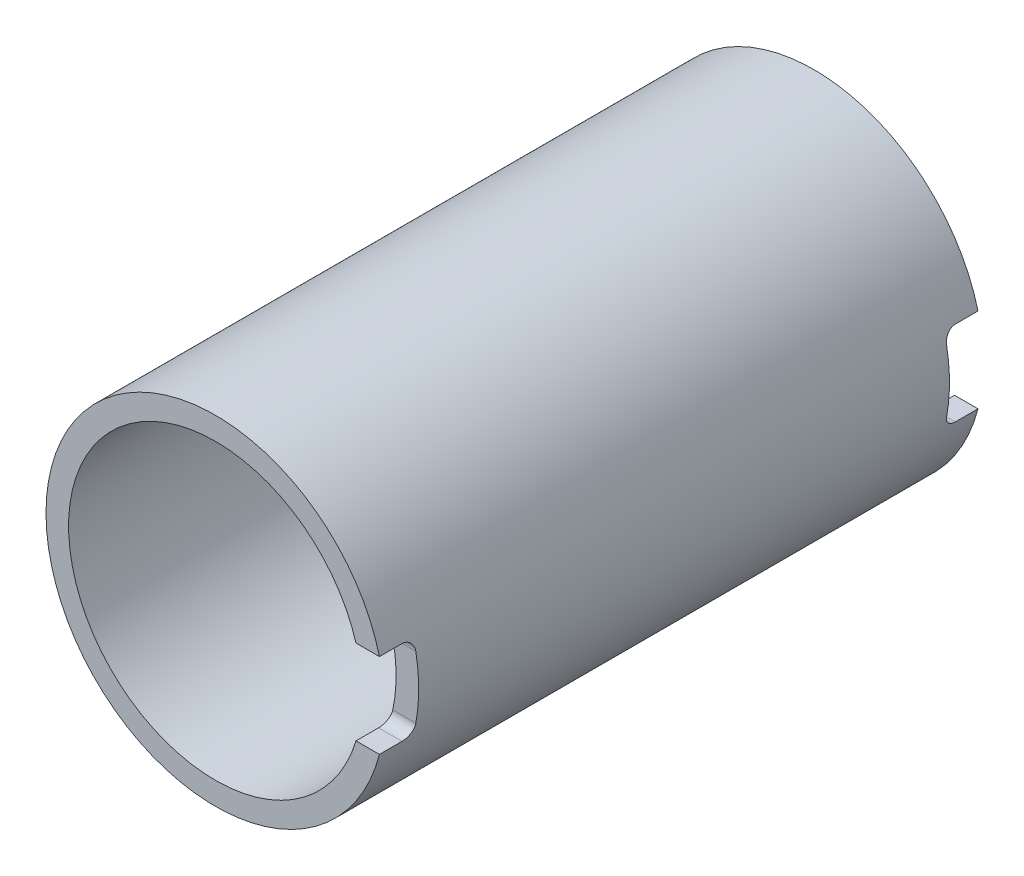
SolidWorks part; units mm, degrees
material "Brass"
ref_plane "Front Plane" through (0, 0, 0) normal (0, 0, 1) x (1, 0, 0)
ref_plane "Top Plane" through (0, 0, 0) normal (0, 1, 0) x (1, 0, 0)
ref_plane "Right Plane" through (0, 0, 0) normal (1, 0, 0) x (0, 0, -1)
sketch "Sketch2" plane through (0, 0, 0) normal (0, 0, 1) x (1, 0, 0)
  circle A0 centre (0, 0) radius 15
  circle A1 centre (0, 0) radius 13
  dimension "D1" = 30
  dimension "D2" = 26
extrude "Boss-Extrude1" add sketch "Sketch2" along normal mid plane 53
sketch "Sketch3" plane through (0, 0, 0) normal (1, 0, 0) x (0, 0, -1)
  line L0 (0, 0) -> (-50000, 0) construction
  line L1 (-26.5, -3.75) -> (-24.5, -3.75)
  line L2 (-26.5, 15) -> (-26.5, -15) construction
  line L3 (-23.5, -2.75) -> (-23.5, 2.75)
  line L4 (-26.5, 3.75) -> (-26.5, -3.75)
  line L5 (-24.5, 3.75) -> (-26.5, 3.75)
  line L6 (0, 0) -> (0, -50000) construction
  line L7 (26.5, -3.75) -> (24.5, -3.75)
  line L8 (23.5, -2.75) -> (23.5, 2.75)
  line L9 (26.5, 3.75) -> (26.5, -3.75)
  line L10 (24.5, 3.75) -> (26.5, 3.75)
  arc A0 (-24.5, -3.75) -> (-23.5, -2.75) centre (-24.5, -2.75) ccw
  arc A1 (-23.5, 2.75) -> (-24.5, 3.75) centre (-24.5, 2.75) ccw
  arc A2 (24.5, -3.75) -> (23.5, -2.75) centre (24.5, -2.75) cw
  arc A3 (23.5, 2.75) -> (24.5, 3.75) centre (24.5, 2.75) cw
  point P9 (-23.5, 0)
  dimension "D2" = 1
  dimension "D1" = 3
  dimension "7.5" = 7.5
extrude "Cut-Extrude1" cut sketch "Sketch3" along normal up to next
